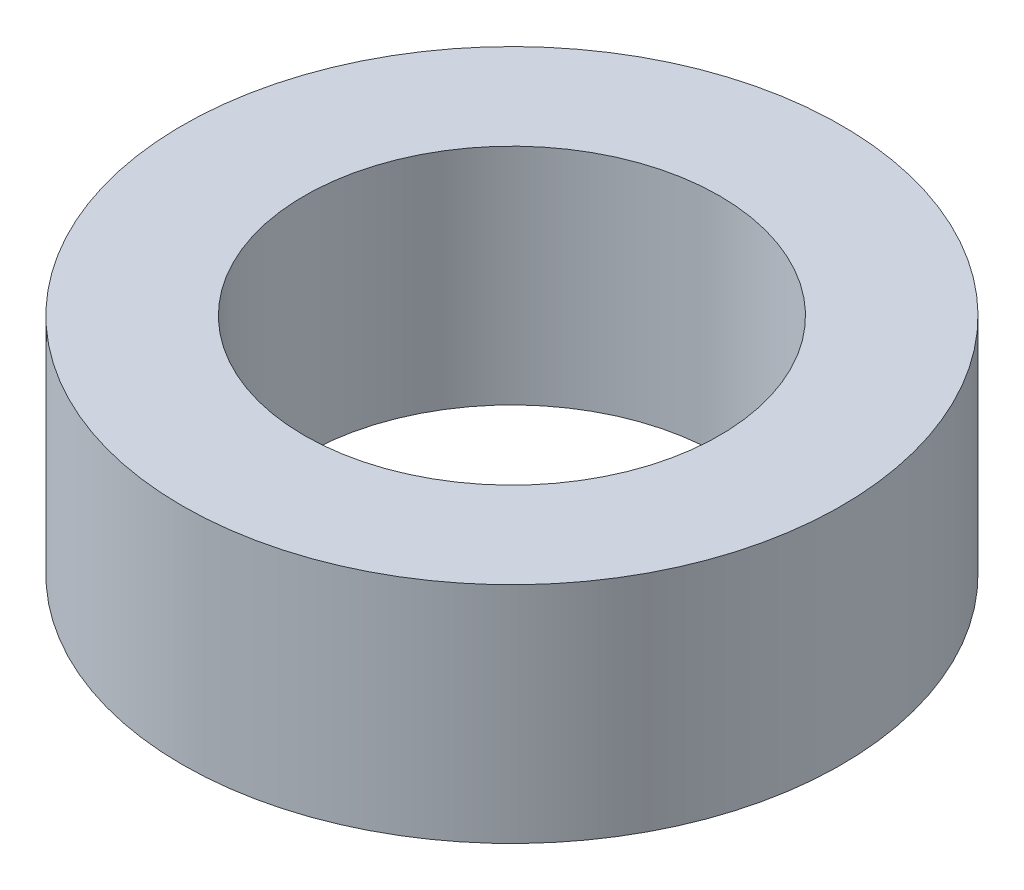
SolidWorks part; units mm, degrees
ref_plane "Front Plane" through (0, 0, 0) normal (0, 0, 1) x (1, 0, 0)
ref_plane "Top Plane" through (0, 0, 0) normal (0, 1, 0) x (1, 0, 0)
ref_plane "Right Plane" through (0, 0, 0) normal (1, 0, 0) x (0, 0, -1)
sketch "Sketch1" plane through (0, 0, 0) normal (0, 1, 0) x (1, 0, 0)
  circle A0 centre (0, 0) radius 6.35
  dimension "D1" = 12.7
extrude "Boss-Extrude1" add sketch "Sketch1" along normal blind 4.318
sketch "Sketch2" plane through (0, 4.318, 0) normal (0, 1, 0) x (1, 0, 0)
  circle A0 centre (0, 0) radius 4
  dimension "D1" = 8
sketch "Sketch3" plane through (0, 4.318, 0) normal (0, 1, 0) x (1, 0, 0)
  circle A0 centre (0, 0) radius 4
  dimension "D1" = 8
extrude "Cut-Extrude2" cut sketch "Sketch3" against normal through all
